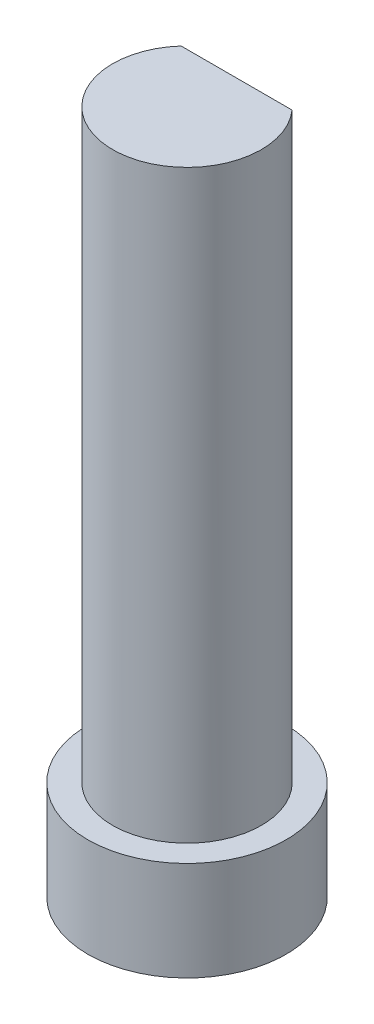
SolidWorks part; units mm, degrees
ref_plane "Alzado" through (0, 0, 0) normal (0, 0, 1) x (1, 0, 0)
ref_plane "Planta" through (0, 0, 0) normal (0, 1, 0) x (1, 0, 0)
ref_plane "Vista lateral" through (0, 0, 0) normal (1, 0, 0) x (0, 0, -1)
sketch "Croquis1" plane through (0, 0, 0) normal (0, 1, 0) x (1, 0, 0)
  circle A0 centre (0, 0) radius 2
extrude "Saliente-Extruir1" add sketch "Croquis1" along normal blind 2
sketch "Croquis2" plane through (0, 0, 0) normal (0, -1, 0) x (1, 0, 0)
  circle A0 centre (0, 0) radius 0.2
extrude "Cortar-Extruir1" cut sketch "Croquis2" against normal blind 2
sketch "Croquis3" plane through (0, 2, 0) normal (0, 1, 0) x (1, 0, 0)
  circle A0 centre (0, 0) radius 1.5
extrude "Saliente-Extruir2" add sketch "Croquis3" along normal blind 11.8 separate body
sketch "Croquis5" plane through (0, 13.8, 0) normal (0, 1, 0) x (1, 0, 0)
  line L0 (0, 0) -> (0, -1.5) construction
  line L1 (0, 0) -> (0, 1) construction
  line L2 (0, 1) -> (1.118, 1)
  line L3 (0, 1) -> (-1.118, 1)
  circle A0 centre (0, 0) radius 1.5 construction
  circle A2 centre (0, 0) radius 1.5
  arc A3 (1.118, 1) -> (-1.118, 1) centre (0, 0) ccw
  dimension "D1" = 0
extrude "Cortar-Extruir2" cut sketch "Croquis5" against normal blind 9.5
